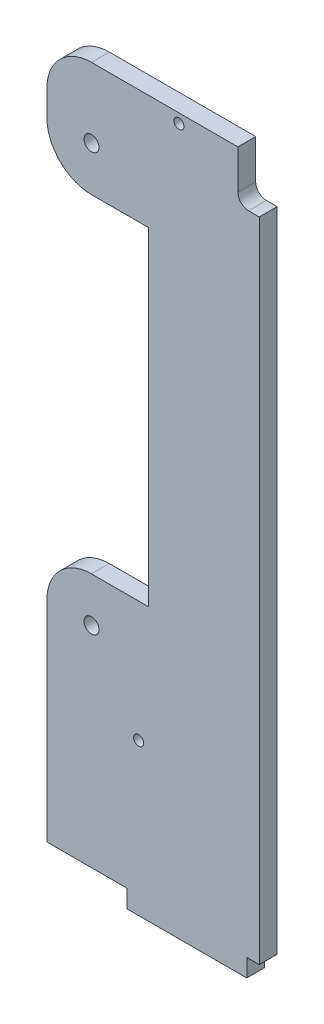
SolidWorks part; units mm, degrees
material "6061-T6 Black anodised"
ref_plane "Front Plane" through (0, 0, 0) normal (0, 0, 1) x (1, 0, 0)
ref_plane "Top Plane" through (0, 0, 0) normal (0, 1, 0) x (1, 0, 0)
ref_plane "Right Plane" through (0, 0, 0) normal (1, 0, 0) x (0, 0, -1)
sketch "Sketch1" plane through (0, 0, 0) normal (0, 0, 1) x (1, 0, 0)
  line L0 (41, 136.6) -> (41, 125.6)
  line L1 (10, -58.8) -> (-12.5, -58.8)
  line L2 (-12.5, 124.1) -> (-12.5, 117)
  line L3 (10, -29.8) -> (47, -29.8) construction
  line L4 (47, 122.6) -> (47, -29.8)
  line L5 (44, 122.6) -> (47, 122.6)
  line L6 (41, 136.6) -> (37.5, 136.6)
  line L7 (-12.5, -58.8) -> (-12.5, 0)
  line L10 (0, 12.5) -> (16, 12.5)
  line L11 (16, 12.5) -> (16, 104.5)
  line L12 (16, 104.5) -> (0, 104.5)
  line L13 (47, -29.8) -> (47, -58.8)
  line L16 (43.5, -63.8) -> (10, -63.8)
  line L17 (10, -63.8) -> (10, -58.8)
  line L18 (43.5, -58.8) -> (47, -58.8)
  line L19 (43.5, -58.8) -> (43.5, -63.8)
  line L20 (0, 136.6) -> (37.5, 136.6)
  circle A0 centre (0, 0) radius 2.1
  circle A1 centre (0, 117) radius 2.1
  arc A2 (41, 125.6) -> (44, 122.6) centre (44, 125.6) ccw
  arc A3 (0, 12.5) -> (-12.5, 0) centre (0, 0) ccw
  arc A4 (-12.5, 117) -> (0, 104.5) centre (0, 117) ccw
  arc A5 (0, 136.6) -> (-12.5, 124.1) centre (0, 124.1) ccw
  dimension "D6" = 3
  dimension "D19" = 4.2
  dimension "D1" = 12.5
  dimension "D2" = 117
  dimension "D3" = 29.8
  dimension "D5" = 47
  dimension "D7" = 6
  dimension "D9" = 14
  dimension "D12" = 28.5
  dimension "D13" = 34
  dimension "D17" = 5
  dimension "D18" = 3.5
extrude "Boss-Extrude1" add sketch "Sketch1" along normal blind 5
sketch "Sketch2" plane through (0, 0, 5) normal (0, 0, 1) x (1, 0, 0)
  circle A0 centre (13.2, -21.3) radius 1.4
  circle A1 centre (24.5, 134) radius 1.4
  circle A2 centre (0, 117) radius 2.1 construction
  dimension "D2" = 13.2
  dimension "D3" = 2.8
  dimension "D5" = 17
  dimension "D1" = 21.3
  dimension "D4" = 24.5
extrude "Cut-Extrude1" cut sketch "Sketch2" against normal through all
